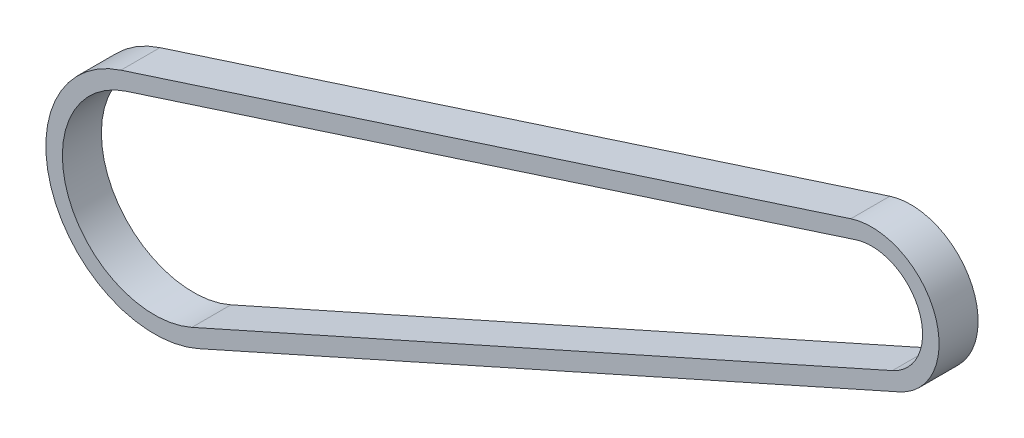
SolidWorks part; units mm, degrees
ref_plane "Front Plane" through (0, 0, 0) normal (0, 0, 1) x (1, 0, 0)
ref_plane "Top Plane" through (0, 0, 0) normal (0, 1, 0) x (1, 0, 0)
ref_plane "Right Plane" through (0, 0, 0) normal (1, 0, 0) x (0, 0, -1)
sketch "Sketch2" plane through (0, 0, 0) normal (0, 0, 1) x (1, 0, 0)
  line L0 (0, 0) -> (1, 0) construction
  line L1 (0, 0) -> (0, 1) construction
  line L2 (5.6403, -12.631) -> (-155.9106, -84.7705)
  line L3 (-172.5867, -41.3278) -> (-4.2602, 13.1607)
  arc A0 (-4.2602, 13.1607) -> (5.6403, -12.631) centre (0, 0) cw
  arc A1 (-155.9106, -84.7705) -> (-172.5867, -41.3278) centre (-165.4109, -63.4953) cw
extrude "Extrude-Thin1" add sketch "Sketch2" along normal mid plane 9 thin thin type two direction wall 1.73 second wall 2.08
equation "\"D1@Extrude-Thin1\"=9mm"
equation "\"D5@Extrude-Thin1\"=1.73mm"
equation "\"D6@Extrude-Thin1\"=2.08mm"
